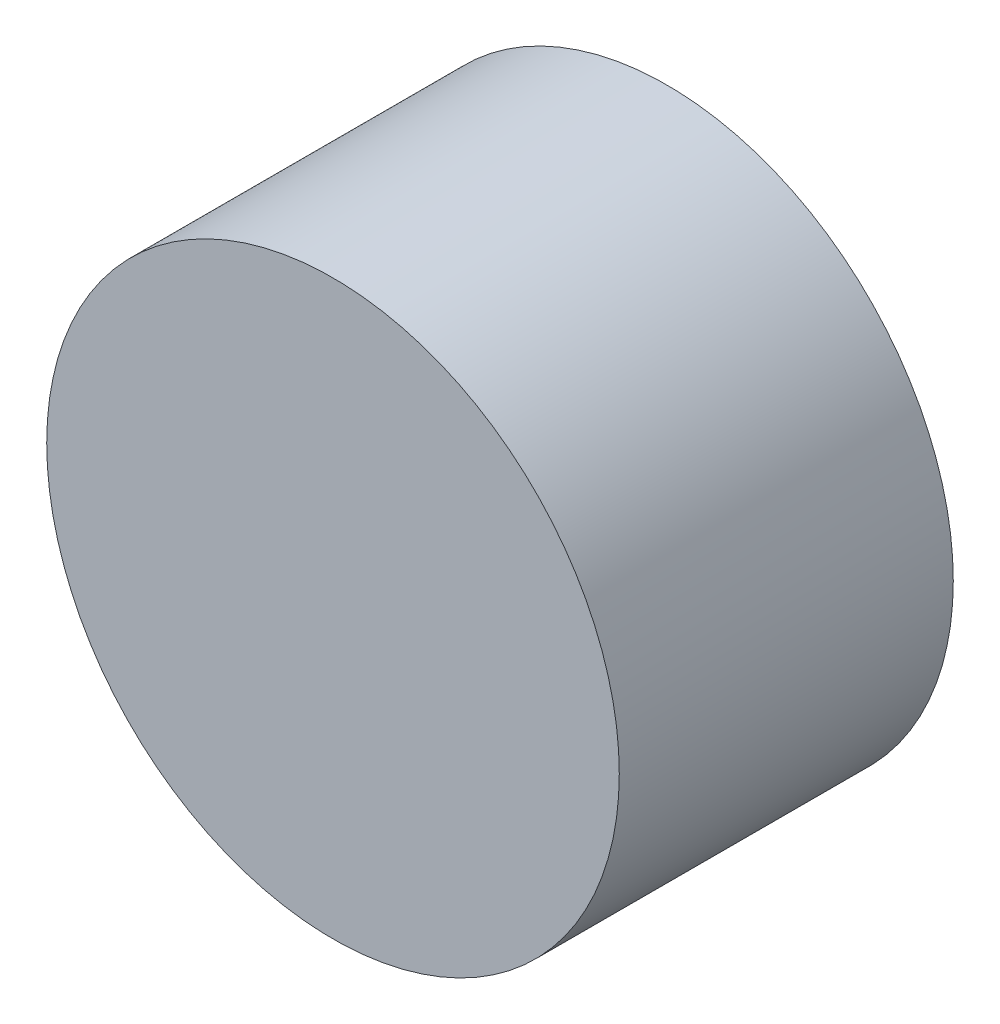
SolidWorks part; units mm, degrees
ref_plane "前视基准面" through (0, 0, 0) normal (0, 0, 1) x (1, 0, 0)
ref_plane "上视基准面" through (0, 0, 0) normal (0, 1, 0) x (1, 0, 0)
ref_plane "右视基准面" through (0, 0, 0) normal (1, 0, 0) x (0, 0, -1)
other "Configuration Table"
sketch "草图1" plane through (0, 0, 0) normal (0, 0, 1) x (1, 0, 0)
  circle A0 centre (0, 0) radius 240
extrude "凸台-拉伸1" add sketch "草图1" along normal blind 280
